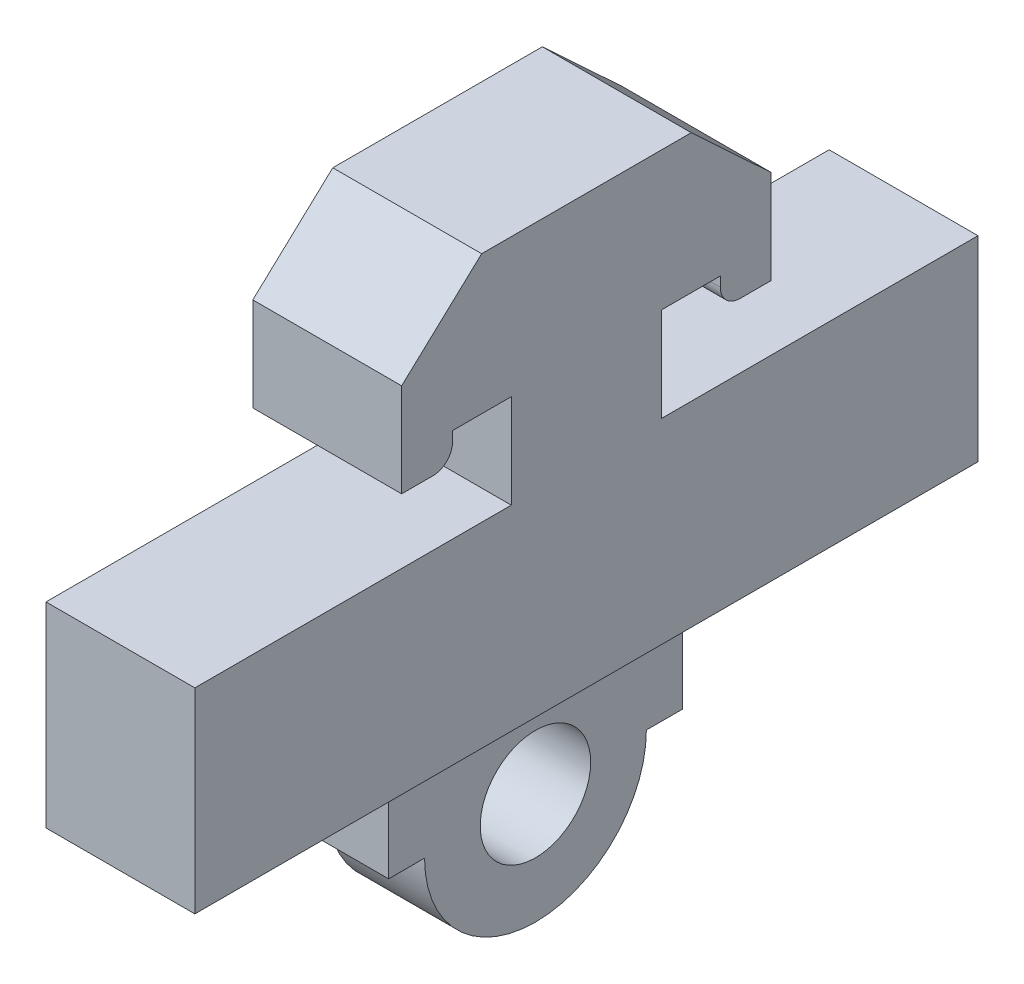
SolidWorks part; units mm, degrees
ref_plane "Front Plane" through (0, 0, 0) normal (0, 0, 1) x (1, 0, 0)
ref_plane "Top Plane" through (0, 0, 0) normal (0, 1, 0) x (1, 0, 0)
ref_plane "Right Plane" through (0, 0, 0) normal (1, 0, 0) x (0, 0, -1)
sketch "Sketch1" plane through (0, 0, 0) normal (0, 1, 0) x (1, 0, 0)
  line L1 (-37.4, -20) -> (37.4, -20)
  line L2 (-37.4, -20) -> (-37.4, 20)
  line L3 (-37.4, 20) -> (37.4, 20)
  line L4 (37.4, -20) -> (37.4, 20)
  line L5 (-37.4, -20) -> (37.4, 20) construction
  line L6 (-37.4, 20) -> (37.4, -20) construction
  point P0 (0, 0)
  dimension "D1" = 40
  dimension "D2" = 74.8
extrude "Boss-Extrude1" add sketch "Sketch1" along normal blind 10
sketch "Sketch2" plane through (37.4, 0, 0) normal (1, 0, 0) x (0, 0, -1)
  line L0 (-7.5, 0) -> (-7.5, -6)
  line L1 (-20, 0) -> (20, 0) construction
  line L2 (-7.5, -6) -> (-5.665, -6)
  line L3 (7.5, -6) -> (7.5, 0)
  line L5 (0, 0) -> (0, 1.9909) construction
  line L6 (5.665, -6) -> (7.5, -6)
  line L7 (-2.82, -6) -> (2.82, -6)
  line L8 (-20, 0) -> (-7.5, 0)
  line L9 (7.5, 0) -> (20, 0)
  line L12 (-20, 0) -> (20, 0)
  line L13 (20, 0) -> (20, 10)
  line L14 (20, 10) -> (-20, 10)
  line L15 (-20, 10) -> (-20, 0)
  line L17 (20, 0) -> (20, 10)
  line L18 (20, 10) -> (-20, 10)
  line L19 (-20, 10) -> (-20, 0)
  circle A0 centre (0, -6) radius 2.82
  arc A1 (-5.665, -6) -> (5.665, -6) centre (0, -6) ccw
  dimension "D1" = 5.64
  dimension "D2" = 11.33
  dimension "D4" = 7.5
  dimension "D3" = 6
  dimension "D5" = 0
extrude "Boss-Extrude2" add sketch "Sketch2" along normal blind 5
mirror "Mirror1" about plane through (0, 0, 0) normal (1, 0, 0) of "Boss-Extrude2"
sketch "Sketch3" plane through (-42.4, 0, 0) normal (-1, 0, 0) x (0, 0, 1)
  line L0 (-4.1618, 10) -> (3.8382, 10)
  line L1 (-20, 10) -> (20, 10) construction
  line L2 (3.8382, 10) -> (3.8382, 14.8)
  line L3 (3.8382, 14.8) -> (6.8382, 14.8)
  line L4 (6.8382, 14.8) -> (6.8382, 14.3)
  line L5 (7.8382, 13.3) -> (9.4382, 13.3)
  line L6 (9.4382, 18.08) -> (9.4382, 14.8)
  line L7 (9.4382, 18.08) -> (5.3521, 21.88)
  line L8 (0, 10) -> (0, 13.289) construction
  line L9 (0, 0) -> (0, 3.0083) construction
  line L10 (9.4382, 14.8) -> (9.4382, 13.3)
  line L11 (-9.4382, 18.08) -> (-5.3521, 21.88)
  line L12 (-9.4382, 18.08) -> (-9.4382, 14.8)
  line L13 (-9.4382, 14.8) -> (-9.4382, 13.3)
  line L14 (-6.8382, 14.8) -> (-6.8382, 14.3)
  line L15 (-7.8382, 13.3) -> (-9.4382, 13.3)
  line L16 (-3.8382, 14.8) -> (-6.8382, 14.8)
  line L17 (-3.8382, 10) -> (-3.8382, 14.8)
  line L18 (-5.3521, 21.88) -> (5.3521, 21.88)
  arc A0 (6.8382, 14.3) -> (7.8382, 13.3) centre (7.8382, 14.3) ccw
  arc A1 (-6.8382, 14.3) -> (-7.8382, 13.3) centre (-7.8382, 14.3) cw
  line M10 (20, 10) -> (-20, 10)
  dimension "D9" = 1
  dimension "D1" = 8
  dimension "D2" = 4.8
  dimension "D3" = 1.5
  dimension "D4" = 3.28
  dimension "D5" = 3.8
  dimension "D6" = 5.58
  dimension "D7" = 2.6
  dimension "D8" = 5.6
extrude "Boss-Extrude3" add sketch "Sketch3" against normal up to surface (84.8 mm away) contours A1 L14 L16 L17 L2 L3 L4 A0 L5 L10 L6 L7 L18 L11 L12 L13 L15 M10 up to face at (42.4, -6, -2.82)
sketch "Sketch4" plane through (0, 21.88, 0) normal (0, 1, 0) x (1, 0, 0)
  line L0 (-42.4, -20) -> (42.4, -20) construction
  line L1 (42.4, 20) -> (-34.7967, 20)
  line L2 (42.4, 20) -> (42.4, -20)
  line L3 (42.4, -20) -> (-34.7967, -20)
  line L4 (-34.7967, 20) -> (-34.7967, -20)
extrude "Cut-Extrude1" cut sketch "Sketch4" against normal blind 59
